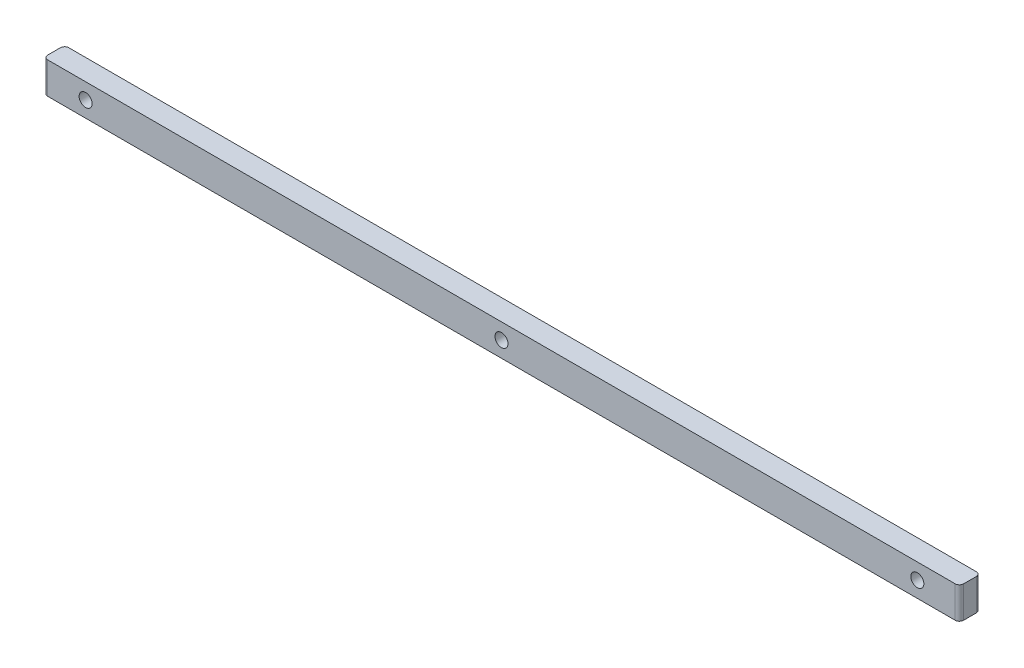
SolidWorks part; units mm, degrees
material "Balsa"
ref_plane "Front Plane" through (0, 0, 0) normal (0, 0, 1) x (1, 0, 0)
ref_plane "Top Plane" through (0, 0, 0) normal (0, 1, 0) x (1, 0, 0)
ref_plane "Right Plane" through (0, 0, 0) normal (1, 0, 0) x (0, 0, -1)
sketch "Sketch1" plane through (0, 0, 0) normal (0, 0, 1) x (1, 0, 0)
  line L1 (-276.225, -9.525) -> (276.225, -9.525)
  line L2 (-276.225, -9.525) -> (-276.225, 9.525)
  line L3 (-276.225, 9.525) -> (276.225, 9.525)
  line L4 (276.225, -9.525) -> (276.225, 9.525)
  line L5 (-276.225, -9.525) -> (276.225, 9.525) construction
  line L6 (-276.225, 9.525) -> (276.225, -9.525) construction
  point P0 (0, 0)
  dimension "D1" = 552.45
  dimension "D2" = 19.05
extrude "Boss-Extrude1" add sketch "Sketch1" along normal mid plane 12.7
sketch "Sketch2" plane through (0, 0, 6.35) normal (0, 0, 1) x (1, 0, 0)
  line L4 (276.225, -9.525) -> (276.225, 9.525)
  line L5 (276.225, 9.525) -> (-276.225, 9.525)
  line L6 (-276.225, 9.525) -> (-276.225, -9.525)
  line L7 (-276.225, -9.525) -> (276.225, -9.525)
  line L8 (276.225, -9.525) -> (276.225, 9.525)
  line L9 (276.225, 9.525) -> (-276.225, 9.525)
  line L10 (-276.225, 9.525) -> (-276.225, -9.525)
  line L11 (-276.225, -9.525) -> (276.225, -9.525)
  circle A0 centre (0, 0) radius 3.937
  circle A1 centre (250.825, 0) radius 3.937
  circle A2 centre (-250.825, 0) radius 3.937
  point P11 (0, 0)
  point P12 (0, 0)
  point P13 (0, 0)
  dimension "D2" = 7.874
  dimension "D3" = 250.825
  dimension "D4" = 250.825
  dimension "D5" = 9.525
  dimension "D6" = 9.525
  dimension "D1" = 0
extrude "Cut-Extrude1" cut sketch "Sketch2" against normal through all both and the other way through all contours A2 | A0 | A1
fillet "Fillet1" radius 2.54 4 edges at (-276.225, 0, -6.35) (-276.225, 0, 6.35) (276.225, 0, -6.35) (276.225, 0, 6.35)
